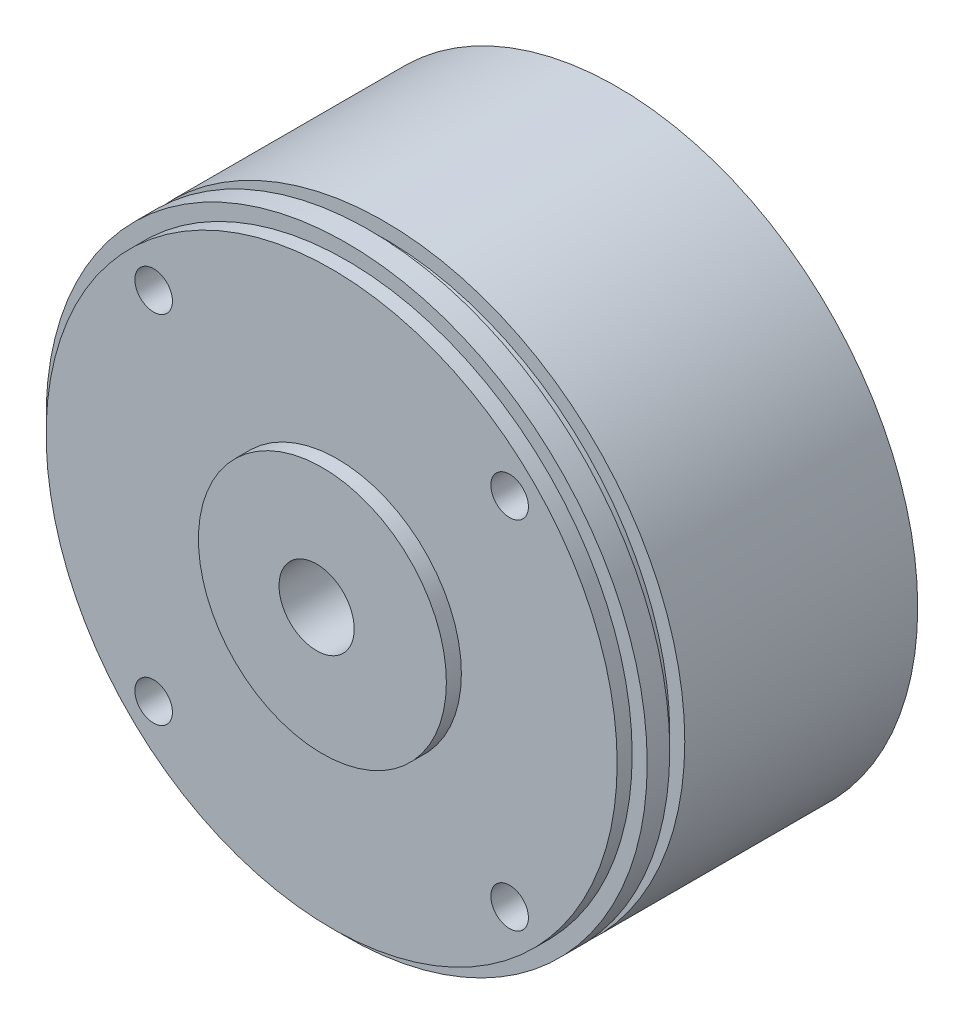
SolidWorks part; units mm, degrees
ref_plane "前视基准面" through (0, 0, 0) normal (0, 0, 1) x (1, 0, 0)
ref_plane "上视基准面" through (0, 0, 0) normal (0, 1, 0) x (1, 0, 0)
ref_plane "右视基准面" through (0, 0, 0) normal (1, 0, 0) x (0, 0, -1)
sketch "草图1" plane through (0, 0, 0) normal (0, 0, 1) x (1, 0, 0)
  circle A0 centre (0, 0) radius 20
  dimension "D1" = 40
extrude "凸台-拉伸1" add sketch "草图1" along normal blind 20
sketch "草图2" plane through (0, 0, 0) normal (0, 0, 1) x (1, 0, 0)
  circle A0 centre (0, 0) radius 15
  dimension "D1" = 30
extrude "凸台-拉伸2" add sketch "草图2" against normal blind 0.5
sketch "草图3" plane through (0, 0, 0) normal (0, 0, 1) x (1, 0, 0)
  circle A0 centre (0, 0) radius 10 construction
  circle A1 centre (0, 10) radius 1.5
  circle A2 centre (10, 0) radius 1.5
  circle A3 centre (0, -10) radius 1.5
  circle A4 centre (-10, 0) radius 1.5
  dimension "D1" = 20
  dimension "D2" = 3
  dimension "D3" = 4
extrude "切除-拉伸2" cut sketch "草图3" along normal blind 4 and the other way blind 4
ref_plane "基准面1" through (0, 0, 20) normal (0, 0, 1) x (1, 0, 0)
sketch "草图4" plane through (0, 0, 20) normal (0, 0, 1) x (1, 0, 0)
  circle A0 centre (0.385, 0) radius 8.25
  circle A1 centre (0, 0) radius 20
  dimension "D1" = 16.5
extrude "切除-拉伸3" cut sketch "草图4" against normal blind 1
sketch "草图5" plane through (0, 0, 20) normal (0, 0, 1) x (1, 0, 0)
  circle A0 centre (0, 0) radius 19
  circle A1 centre (0, 0) radius 20
  dimension "D1" = 38
extrude "切除-拉伸4" cut sketch "草图5" against normal blind 2
ref_plane "基准面2" through (0, 0, 16.5) normal (0, 0, 1) x (1, 0, 0)
sketch "草图6" plane through (0, 0, 16.5) normal (0, 0, 1) x (1, 0, 0)
  circle A0 centre (0, 0) radius 19
  circle A1 centre (0, 0) radius 20
extrude "切除-拉伸5" cut sketch "草图6" against normal blind 1
sketch "草图7" plane through (0, 0, 20) normal (0, 0, 1) x (1, 0, 0)
  line L1 (11.844, 11.844) -> (-11.844, 11.844) construction
  line L2 (11.844, 11.844) -> (11.844, -11.844) construction
  line L3 (11.844, -11.844) -> (-11.844, -11.844) construction
  line L4 (-11.844, 11.844) -> (-11.844, -11.844) construction
  line L5 (11.844, 11.844) -> (-11.844, -11.844) construction
  line L6 (11.844, -11.844) -> (-11.844, 11.844) construction
  circle A0 centre (0, 0) radius 16.75 construction
  circle A1 centre (-11.844, -11.844) radius 1.25
  circle A2 centre (-11.844, 11.844) radius 1.25
  circle A3 centre (11.844, 11.844) radius 1.25
  circle A4 centre (11.844, -11.844) radius 1.25
  dimension "D1" = 33.5
  dimension "D2" = 2.5
  dimension "D3" = 4
extrude "切除-拉伸6" cut sketch "草图7" against normal blind 5
sketch "草图8" plane through (0, 0, 0) normal (0, 0, 1) x (1, 0, 0)
  circle A0 centre (0, 0) radius 6.3
  dimension "D1" = 12.6
extrude "切除-拉伸7" cut sketch "草图8" along normal blind 5 and the other way through all
sketch "草图9" plane through (0, 0, 0) normal (0, 0, 1) x (1, 0, 0)
  circle A0 centre (0, 0) radius 2.5
  dimension "D1" = 5
extrude "切除-拉伸8" cut sketch "草图9" against normal through all both and the other way through all
